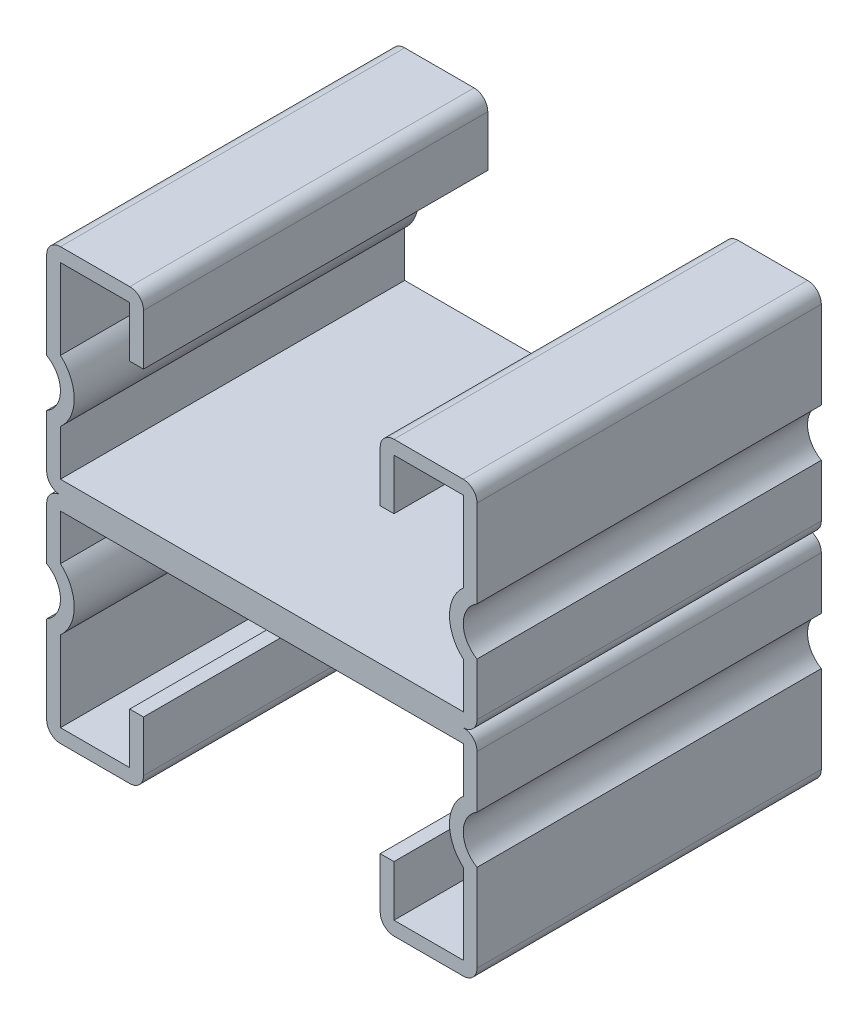
SolidWorks part; units mm, degrees
ref_plane "Plane1" through (0, 0, 0) normal (0, 0, 1) x (1, 0, 0)
ref_plane "Plane2" through (0, 0, 0) normal (0, 1, 0) x (1, 0, 0)
ref_plane "Plane3" through (0, 0, 0) normal (1, 0, 0) x (0, 0, -1)
sketch "Sketch1" plane through (0, 0, 0) normal (0, 0, 1) x (1, 0, 0)
  line L0 (-15.875, 14.859) -> (-15.875, 8.4146)
  line L1 (-15.875, 4.895) -> (-15.875, 1.016)
  line L2 (-14.859, 0) -> (14.859, 0)
  line L3 (15.875, 1.016) -> (15.875, 4.895)
  line L4 (15.875, 8.4146) -> (15.875, 14.859)
  line L5 (14.859, 15.875) -> (9.7472, 15.875)
  line L6 (8.7312, 14.859) -> (8.7312, 11.1125)
  line L7 (-14.859, 15.875) -> (-9.7473, 15.875)
  line L8 (-8.7313, 14.859) -> (-8.7313, 11.1125)
  line L9 (14.859, 2.6995) -> (14.859, 6.4516) construction
  line L10 (-14.859, 14.6685) -> (-14.859, 2.6995) construction
  line L11 (-9.7473, 14.859) -> (-9.7473, 11.1125)
  line L12 (-14.859, 14.859) -> (-9.7473, 14.859)
  line L13 (-14.859, 14.859) -> (-14.859, 8.9266)
  line L14 (-14.859, 4.383) -> (-14.859, 1.016)
  line L15 (-14.859, 1.016) -> (14.859, 1.016)
  line L16 (14.859, 1.016) -> (14.859, 4.383)
  line L17 (14.859, 8.9266) -> (14.859, 14.859)
  line L18 (14.859, 14.859) -> (9.7472, 14.859)
  line L19 (9.7472, 14.859) -> (9.7472, 11.1125)
  line L20 (-9.7473, 11.1125) -> (-8.7313, 11.1125)
  line L21 (8.7312, 11.1125) -> (9.7472, 11.1125)
  arc A0 (15.875, 8.4146) -> (15.875, 4.895) centre (16.891, 6.6548) ccw
  arc A1 (-15.875, 4.895) -> (-15.875, 8.4146) centre (-16.891, 6.6548) ccw
  arc A2 (-9.7473, 15.875) -> (-8.7313, 14.859) centre (-9.7473, 14.859) cw
  arc A3 (-15.875, 14.859) -> (-14.859, 15.875) centre (-14.859, 14.859) cw
  arc A4 (-14.859, 0) -> (-15.875, 1.016) centre (-14.859, 1.016) cw
  arc A5 (15.875, 1.016) -> (14.859, 0) centre (14.859, 1.016) cw
  arc A6 (14.859, 15.875) -> (15.875, 14.859) centre (14.859, 14.859) cw
  arc A7 (8.7312, 14.859) -> (9.7472, 15.875) centre (9.7472, 14.859) cw
  arc A8 (-14.859, 4.383) -> (-14.859, 8.9266) centre (-16.891, 6.6548) ccw
  arc A9 (14.859, 8.9266) -> (14.859, 4.383) centre (16.891, 6.6548) ccw
  dimension "D9" = 2.032
  dimension "D10" = 2.032
  dimension "Width" = 31.75
  dimension "D6" = 17.4625
  dimension "edge" = 7.1437
  dimension "Lip" = 4.7625
  dimension "D1" = 15.875
  dimension "D2" = 6.6548
  dimension "gauge" = 1.016
extrude "Base-Extrude" add sketch "Sketch1" along normal mid plane 25.4
mirror "Mirror1" about plane through (0, 0, 0) normal (0, 1, 0) of "Base-Extrude"
equation "\"D1@Sketch1\" = \"Width@Sketch1\" / 2"
equation "\"D6@Sketch1\" = \"Width@Sketch1\" - 2 * \"edge@Sketch1\""
equation "\"D10@Sketch1\" = 2 * \"gauge@Sketch1\""
equation "\"D9@Sketch1\" = \"D10@Sketch1\""
